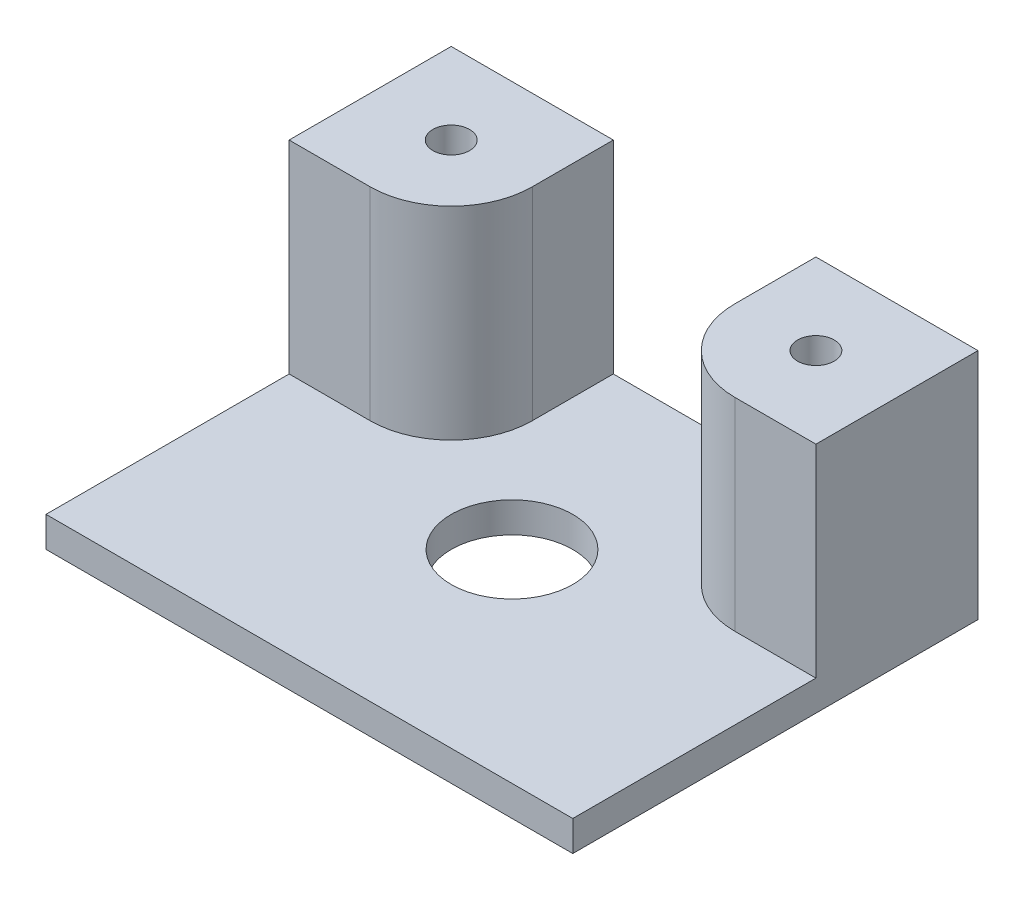
SolidWorks part; units mm, degrees
material "AISI 1020"
ref_plane "Front Plane" through (0, 0, 0) normal (0, 0, 1) x (1, 0, 0)
ref_plane "Top Plane" through (0, 0, 0) normal (0, 1, 0) x (1, 0, 0)
ref_plane "Right Plane" through (0, 0, 0) normal (1, 0, 0) x (0, 0, -1)
sketch "Sketch1" plane through (0, 0, 0) normal (0, 1, 0) x (1, 0, 0)
  line L1 (82.55, -63.5) -> (-82.55, -63.5)
  line L2 (82.55, -63.5) -> (82.55, 63.5)
  line L3 (82.55, 63.5) -> (-82.55, 63.5)
  line L4 (-82.55, -63.5) -> (-82.55, 63.5)
  line L5 (82.55, -63.5) -> (-82.55, 63.5) construction
  line L6 (82.55, 63.5) -> (-82.55, -63.5) construction
  point P0 (0, 0)
  dimension "D1" = 165.1
  dimension "D2" = 127
extrude "Base Extrude" add sketch "Sketch1" along normal blind 9.525
sketch "Sketch2" plane through (0, 9.525, 0) normal (0, 1, 0) x (1, 0, 0)
  circle A0 centre (0, 0) radius 19.05
extrude "Center Hole" cut sketch "Sketch2" against normal through all
sketch "Sketch3" plane through (0, 9.525, 0) normal (0, 1, 0) x (1, 0, 0)
  line L1 (-82.55, 63.5) -> (-31.75, 63.5)
  line L2 (-82.55, 63.5) -> (-82.55, 12.7)
  line L3 (-82.55, 12.7) -> (-31.75, 12.7)
  line L4 (-31.75, 63.5) -> (-31.75, 12.7)
  dimension "D1" = 50.8
  dimension "D2" = 50.8
extrude "Tower Extrude" add sketch "Sketch3" along normal blind 63.5
fillet "Fillet" radius 25.4 1 edges at (-31.75, 41.275, -12.7)
sketch "Sketch" plane through (0, 73.025, 0) normal (0, 1, 0) x (1, 0, 0)
  point P0 (-57.15, 38.1)
hole_wizard "1/2-20 Tapped Hole" positions "3DSketch1" profile "Sketch7" tap size "1/2-20" standard "ANSI Inch"
sketch3d "3DSketch1"
  point P0 (-57.15, 73.025, -38.1)
sketch "Sketch7" plane through (-57.15, 73.025, -38.1) normal (1, 0, 0) x (0, 0, 1)
  line L0 (0, 0) -> (0, 35.2076)
  line L1 (0, 35.2076) -> (5.7544, 31.75)
  line L2 (5.7544, 31.75) -> (5.7544, 0)
  line L5 (5.7544, 0) -> (0, 0)
  line L10 (0, 35.2076) -> (-5.7544, 31.75) construction
  line L11 (0, -6.35) -> (0, 107.95) construction
  dimension "Tap Drill Dia." = 11.5087
  dimension "Tap Drill Depth" = 31.75
  dimension "Drill Angle" = 118
cosmetic thread "Hole Thread4" parameters "D1"=25.4, "D2"=12.7
mirror "Mirror" about plane through (0, 0, 0) normal (1, 0, 0) of "Fillet", "Tower Extrude", "1/2-20 Tapped Hole"
